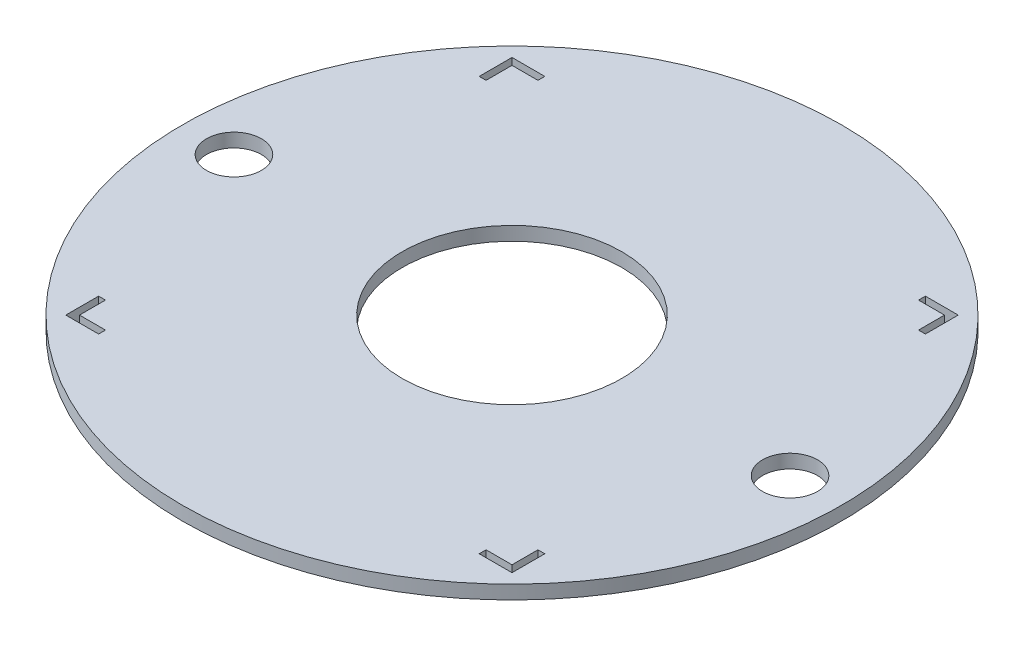
SolidWorks part; units mm, degrees
material "PE Low/Medium Density"
ref_plane "Front Plane" through (0, 0, 0) normal (0, 0, 1) x (1, 0, 0)
ref_plane "Top Plane" through (0, 0, 0) normal (0, 1, 0) x (1, 0, 0)
ref_plane "Right Plane" through (0, 0, 0) normal (1, 0, 0) x (0, 0, -1)
sketch "Sketch1" plane through (0, 0, 0) normal (0, 1, 0) x (1, 0, 0)
  line L0 (-50, 50) -> (-50, 44)
  line L1 (-50, -50) -> (50, -50) construction
  line L2 (-50, -50) -> (-50, 50) construction
  line L3 (-50, 50) -> (50, 50) construction
  line L4 (50, -50) -> (50, 50) construction
  line L5 (-50, -50) -> (50, 50) construction
  line L6 (-50, 50) -> (50, -50) construction
  line L7 (-50, 50) -> (-44, 50)
  line L8 (-51.5875, 51.5875) -> (-51.5875, 44)
  line L9 (-51.5875, 51.5875) -> (-44, 51.5875)
  line L10 (-51.5875, 44) -> (-50, 44)
  line L11 (-44, 51.5875) -> (-44, 50)
  line L12 (-50, 50) -> (-51.5875, 51.5875) construction
  line L13 (0, 0) -> (-50, 0) construction
  line L14 (51.5875, -44) -> (50, -44)
  line L15 (50, -50) -> (50, -44)
  line L16 (51.5875, -51.5875) -> (51.5875, -44)
  line L17 (51.5875, -51.5875) -> (44, -51.5875)
  line L18 (44, -51.5875) -> (44, -50)
  line L19 (50, -50) -> (44, -50)
  line L20 (-50, -50) -> (-44, -50)
  line L21 (-44, -51.5875) -> (-44, -50)
  line L22 (-51.5875, -51.5875) -> (-44, -51.5875)
  line L23 (-51.5875, -51.5875) -> (-51.5875, -44)
  line L24 (-51.5875, -44) -> (-50, -44)
  line L25 (-50, -50) -> (-50, -44)
  line L26 (51.5875, 51.5875) -> (44, 51.5875)
  line L27 (44, 51.5875) -> (44, 50)
  line L28 (50, 50) -> (44, 50)
  line L29 (50, 50) -> (50, 44)
  line L30 (51.5875, 51.5875) -> (51.5875, 44)
  line L31 (51.5875, 44) -> (50, 44)
  circle A0 centre (0, 0) radius 76.2
  dimension "D1" = 152.4
  dimension "D2" = 100
  dimension "D3" = 100
  dimension "D4" = 1.5875
  dimension "D5" = 1.5875
  dimension "D6" = 1.5875
extrude "Boss-Extrude1" add sketch "Sketch1" along normal blind 3.175
sketch "Sketch2" plane through (0, 3.175, 0) normal (0, 1, 0) x (1, 0, 0)
  circle A0 centre (0, 0) radius 25.4
  dimension "D1" = 50.8
extrude "Cut-Extrude1" cut sketch "Sketch2" against normal blind 3.175
sketch "Sketch3" plane through (0, 3.175, 0) normal (0, 1, 0) x (1, 0, 0)
  line L0 (-51.5875, 0) -> (-64.2875, 0) construction
  line L1 (-51.5875, 51.5875) -> (51.5875, 51.5875) construction
  line L2 (-51.5875, 51.5875) -> (-51.5875, -51.5875) construction
  line L3 (-51.5875, -51.5875) -> (51.5875, -51.5875) construction
  line L4 (51.5875, 51.5875) -> (51.5875, -51.5875) construction
  line L5 (51.5875, 0) -> (64.2875, 0) construction
  circle A0 centre (-64.2875, 0) radius 6.35
  circle A1 centre (64.2875, 0) radius 6.35
  dimension "D1" = 12.7
  dimension "D2" = 12.7
extrude "Cut-Extrude2" cut sketch "Sketch3" against normal blind 10
